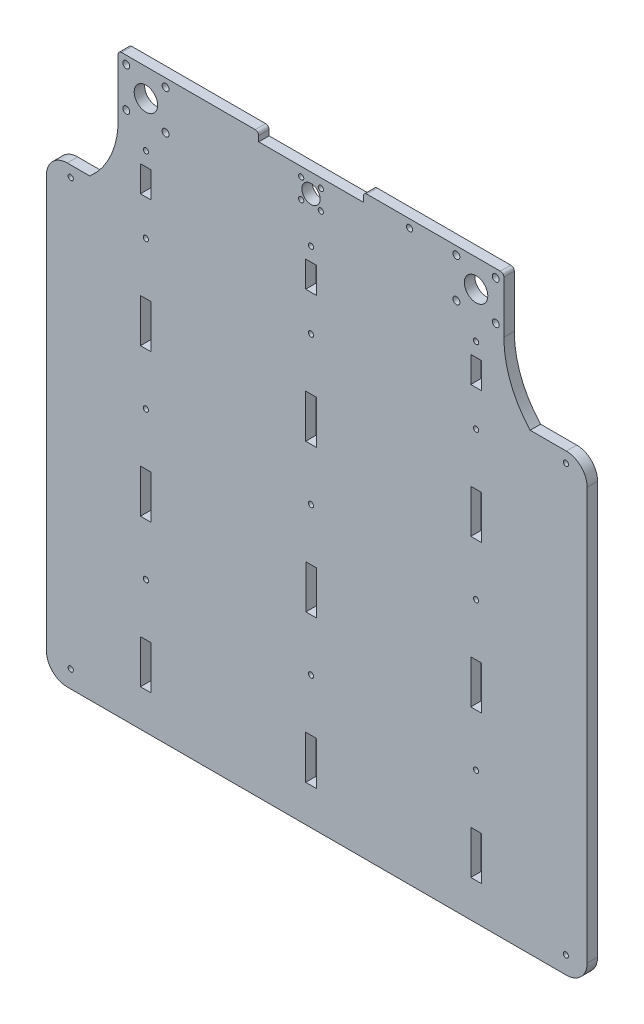
SolidWorks part; units mm, degrees
ref_plane "Alzado" through (0, 0, 0) normal (0, 0, 1) x (1, 0, 0)
ref_plane "Planta" through (0, 0, 0) normal (0, 1, 0) x (1, 0, 0)
ref_plane "Vista lateral" through (0, 0, 0) normal (1, 0, 0) x (0, 0, -1)
sketch "Croquis1" plane through (0, 0, 0) normal (0, 0, 1) x (1, 0, 0)
  line L0 (32.1154, 16) -> (87.6356, 16)
  line L1 (-109, 16) -> (-87.6356, 16)
  line L2 (-111, 14) -> (-111, -16)
  line L3 (-135.2776, -315.9124) -> (-119.3643, -315.9124)
  line L4 (-87.6356, 16) -> (-44.6644, 16)
  line L5 (30.1154, 14) -> (30.1154, 10.91)
  line L6 (0, 0) -> (0, 78.8056) construction
  line L7 (30.1154, 10.91) -> (-30.1154, 10.91)
  line L8 (-111, 0) -> (-111, -16)
  line L9 (-111, -16) -> (-111, 16)
  line L10 (-44.6644, 16) -> (-32.1154, 16)
  line L11 (-119.3643, -315.9124) -> (119.3644, -315.9124)
  line L12 (111, 14) -> (111, -16)
  line L13 (109, 16) -> (87.6356, 16)
  line L14 (-30.1154, 14) -> (-30.1154, 10.91)
  line L15 (-8.3, -8.3) -> (8.3, 8.3) construction
  line L16 (-127.2776, -54.7017) -> (126.134, -54.7017) construction
  line L17 (-95, 0) -> (-95, -315.9124) construction
  line L18 (119.3644, -315.9124) -> (130.2951, -315.9124)
  line L19 (-8.3, 8.3) -> (8.3, -8.3) construction
  line L20 (-127.2776, -54.7017) -> (-135.2776, -54.7017)
  line L21 (-111, 16) -> (-79, -16) construction
  line L22 (-111, -16) -> (-79, 16) construction
  line L23 (-135.2776, -54.7017) -> (-140.2776, -54.7017)
  line L24 (-138.2776, -60.9124) -> (-136.7776, -60.9124) construction
  line L25 (-111, -16) -> (-79, -16) construction
  line L26 (-135.2776, -315.9124) -> (-140.2776, -315.9124)
  line L27 (-152.2776, -66.7017) -> (-152.2776, -303.9124)
  line L28 (-79, -16) -> (111, -16) construction
  line L29 (130.2951, -315.9124) -> (146.9429, -315.9124)
  line L30 (158.9429, -70.771) -> (158.9429, -303.9124)
  line L31 (145.2224, -60.9124) -> (146.7224, -60.9124) construction
  line L32 (126.134, -54.7017) -> (146.9429, -54.7017)
  line L33 (0, 0) -> (0.0001, -316) construction
  line L34 (95, 0) -> (95, -316) construction
  line L35 (158.9429, -66.7017) -> (158.9429, -70.771)
  line L36 (-98.15, -184.7017) -> (-91.95, -184.7017)
  line L37 (-98.15, -34) -> (-91.95, -34)
  line L38 (-98.15, -34) -> (-98.15, -49)
  line L39 (-98.15, -49) -> (-91.95, -49)
  line L40 (-91.95, -34) -> (-91.95, -49)
  line L41 (-98.15, -99.7017) -> (-91.95, -99.7017)
  line L42 (-98.15, -99.7017) -> (-98.15, -124.7017)
  line L43 (-98.15, -124.7017) -> (-91.95, -124.7017)
  line L44 (-91.95, -99.7017) -> (-91.95, -124.7017)
  line L45 (-98.15, -184.7017) -> (-98.15, -209.7017)
  line L46 (-98.15, -209.7017) -> (-91.95, -209.7017)
  line L47 (-91.95, -184.7017) -> (-91.95, -209.7017)
  line L48 (-98.15, -269.7017) -> (-91.95, -269.7017)
  line L49 (-98.15, -269.7017) -> (-98.15, -294.7017)
  line L50 (-98.15, -294.7017) -> (-91.95, -294.7017)
  line L51 (-91.95, -269.7017) -> (-91.95, -294.7017)
  line L52 (-98.15, -99.7017) -> (-98.15, -184.7017) construction
  line L53 (98.15, -99.7017) -> (98.1501, -184.7017) construction
  line L54 (95, 0) -> (95.0001, -315.9124) construction
  line L55 (127.2776, -54.7016) -> (-126.134, -54.7018) construction
  line L56 (91.9501, -269.7017) -> (91.9501, -294.7017)
  line L57 (98.1501, -294.7017) -> (91.9501, -294.7017)
  line L58 (98.1501, -269.7017) -> (98.1501, -294.7017)
  line L59 (98.1501, -269.7017) -> (91.9501, -269.7017)
  line L60 (91.9501, -184.7017) -> (91.9501, -209.7017)
  line L61 (98.1501, -209.7017) -> (91.9501, -209.7017)
  line L62 (98.1501, -184.7017) -> (98.1501, -209.7017)
  line L63 (91.95, -99.7017) -> (91.9501, -124.7017)
  line L64 (98.1501, -124.7017) -> (91.9501, -124.7017)
  line L65 (98.15, -99.7017) -> (98.1501, -124.7017)
  line L66 (98.15, -99.7017) -> (91.95, -99.7017)
  line L67 (91.95, -34) -> (91.95, -49)
  line L68 (98.15, -49) -> (91.95, -49)
  line L69 (98.15, -34) -> (98.15, -49)
  line L70 (98.15, -34) -> (91.95, -34)
  line L71 (98.1501, -184.7017) -> (91.9501, -184.7017)
  line L72 (3.15, -99.7892) -> (3.1501, -184.7892) construction
  line L73 (-3.0499, -269.7892) -> (-3.0499, -294.7892)
  line L74 (3.0501, -294.7892) -> (-3.0499, -294.7892)
  line L75 (3.0501, -269.7892) -> (3.0501, -294.7892)
  line L76 (3.0501, -269.7892) -> (-3.0499, -269.7892)
  line L77 (-2.9499, -184.7892) -> (-2.9499, -209.7892)
  line L78 (3.1501, -209.7892) -> (-2.9499, -209.7892)
  line L79 (3.1501, -184.7892) -> (3.1501, -209.7892)
  line L80 (-3.05, -99.7892) -> (-3.05, -124.7892)
  line L81 (3.15, -124.7892) -> (-3.05, -124.7892)
  line L82 (3.15, -99.7892) -> (3.15, -124.7892)
  line L83 (3.15, -99.7892) -> (-3.05, -99.7892)
  line L84 (-3.05, -34) -> (-3.05, -49)
  line L85 (3.15, -49) -> (-3.05, -49)
  line L86 (3.15, -34) -> (3.15, -49)
  line L87 (3.15, -34) -> (-3.05, -34)
  line L88 (3.1501, -184.7892) -> (-2.9499, -184.7892)
  line L89 (95, -26) -> (-95, -26) construction
  line L90 (83.6863, 11.3137) -> (41.3258, 11.3137) construction
  circle A0 centre (0, 0) radius 5.25
  circle A1 centre (-95, 0) radius 6.75
  circle A2 centre (95, 0) radius 6.75
  circle A3 centre (146.7224, -60.9124) radius 1.5
  circle A4 centre (-83.6863, 11.3137) radius 2
  circle A5 centre (-106.3137, 11.3137) radius 2
  circle A6 centre (-83.6863, -11.3137) radius 2
  circle A7 centre (-106.3137, -11.3137) radius 2
  circle A8 centre (106.3137, -11.3137) radius 2
  circle A9 centre (83.6863, -11.3137) radius 2
  circle A10 centre (83.6863, 11.3137) radius 2
  arc A11 (-111, -16) -> (-127.2776, -54.7017) centre (-158.9474, -18.6077) cw
  arc A12 (111, -16) -> (126.134, -54.7017) centre (168.0523, -16) ccw
  arc A13 (-140.2776, -315.9124) -> (-152.2776, -303.9124) centre (-140.2776, -303.9124) cw
  arc A14 (158.9429, -303.9124) -> (146.9429, -315.9124) centre (146.9429, -303.9124) cw
  arc A15 (158.9429, -66.7017) -> (146.9429, -54.7017) centre (146.9429, -66.7017) ccw
  circle A16 centre (5.6569, 5.6569) radius 1.5
  circle A17 centre (-5.6569, 5.6569) radius 1.5
  circle A18 centre (-5.6569, -5.6569) radius 1.5
  circle A19 centre (5.6569, -5.6569) radius 1.5
  arc A20 (-140.2776, -54.7017) -> (-152.2776, -66.7017) centre (-140.2776, -66.7017) ccw
  circle A21 centre (146.7224, -305.9124) radius 1.5
  circle A22 centre (-138.2776, -305.9124) radius 1.5
  circle A23 centre (-138.2776, -60.9124) radius 1.5
  circle A24 centre (-95, -26) radius 1.5
  circle A25 centre (-95, -69.7017) radius 1.5
  circle A26 centre (-95, -154.7017) radius 1.5
  circle A27 centre (-95, -239.7017) radius 1.5
  circle A28 centre (95.0001, -239.7017) radius 1.5
  arc A29 (109, 16) -> (111, 14) centre (109, 14) cw
  arc A30 (-111, 14) -> (-109, 16) centre (-109, 14) cw
  circle A31 centre (95.0001, -154.7017) radius 1.5
  circle A32 centre (95, -69.7017) radius 1.5
  circle A33 centre (95, -26) radius 1.5
  circle A34 centre (0.0001, -239.7892) radius 1.5
  arc A35 (-32.1154, 16) -> (-30.1154, 14) centre (-32.1154, 14) cw
  circle A36 centre (0.0001, -154.7892) radius 1.5
  circle A37 centre (106.3137, 11.3137) radius 2
  arc A38 (30.1154, 14) -> (32.1154, 16) centre (32.1154, 14) cw
  circle A39 centre (0, -69.7892) radius 1.5
  circle A40 centre (0.0046, -26) radius 1.5
  circle A41 centre (56.6863, 11.3137) radius 1.75
  point P71 (0, 16)
  point P98 (111, 16)
  point P101 (-111, 16)
  point P106 (30.1154, 16)
  point P108 (-147.2776, -54.7017)
  dimension "D3" = 285
  dimension "D4" = 12
  dimension "D5" = 10.5
  dimension "D6" = 14
  dimension "D7" = 285
  dimension "D8" = 13.5
  dimension "D9" = 245
  dimension "D10" = 4
  dimension "D11" = 222
  dimension "D12" = 16
  dimension "D13" = 10
  dimension "D16" = 190
  dimension "D2" = 13.5
  dimension "D18" = 14
  dimension "D21" = 4
  dimension "D19" = 4
  dimension "D20" = 4
  dimension "D22" = 2
  dimension "D24" = 12
  dimension "D25" = 12
  dimension "D34" = 15
  dimension "D45" = 22.6274
  dimension "D14" = 16
  dimension "D15" = 6.2
  dimension "D17" = 95
  dimension "D23" = 20
  dimension "D26" = 5.2532
  dimension "D27" = 5.2532
  dimension "D28" = 11.3137
  dimension "D29" = 11.3137
  dimension "D30" = 11.3137
  dimension "D31" = 11.3137
  dimension "D32" = 15
  dimension "D33" = 8
  dimension "D35" = 25
  dimension "D36" = 30
  dimension "D38" = 85
  dimension "D39" = 10
  dimension "D40" = 10
  dimension "D41" = 20.7017
  dimension "D42" = 6.2
  dimension "D43" = 6.2
  dimension "D44" = 6.2
  dimension "D46" = 27
  dimension "D37" = 3
extrude "Saliente-Extruir1" add sketch "Croquis1" along normal blind 6
